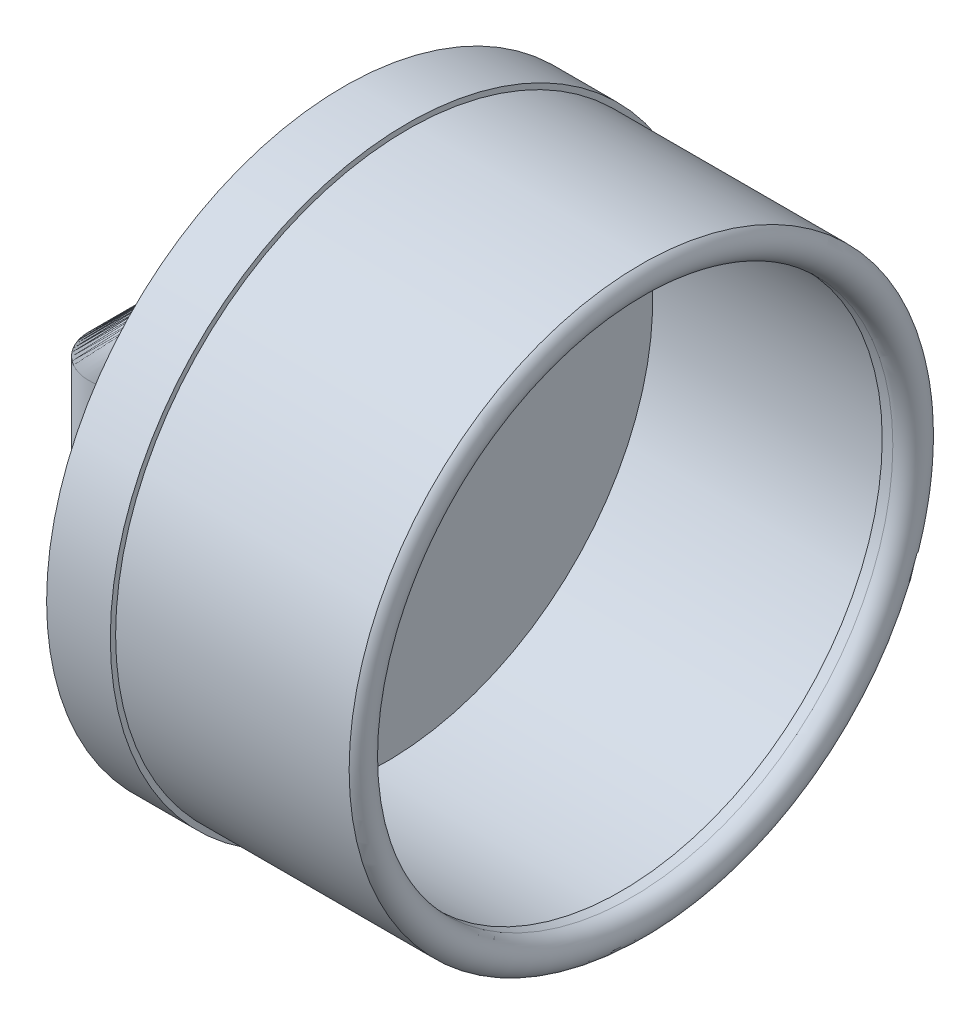
SolidWorks part; units mm, degrees
ref_plane "Front Plane" through (0, 0, 0) normal (0, 0, 1) x (1, 0, 0)
ref_plane "Top Plane" through (0, 0, 0) normal (0, 1, 0) x (1, 0, 0)
ref_plane "Right Plane" through (0, 0, 0) normal (1, 0, 0) x (0, 0, -1)
ref_plane "Plane1" through (0, 0, 0) normal (0, 0, -1) x (-1, 0, 0)
sketch "Sketch1" plane through (0, 0, 0) normal (0, 0, -1) x (-1, 0, 0)
  line L0 (-11.9728, 3.7667) -> (-11.9728, 4.0167)
  line L1 (-11.9728, 4.0167) -> (-0.9121, 4.0167)
  line L2 (-0.9121, 4.0167) -> (-0.9121, 5.4667)
  line L3 (-0.9121, 5.4667) -> (-1.9121, 5.4667)
  line L4 (-1.9121, 5.4667) -> (-1.9121, 5.2167)
  line L5 (-1.9121, 5.2167) -> (-12.9121, 5.2167)
  line L6 (-12.4728, 3.7667) -> (-11.9728, 3.7667)
  line L7 (-12.1757, -8.5333) -> (0.2029, -8.5333) construction
  arc A0 (-12.9121, 5.2167) -> (-12.4728, 3.7667) centre (-12.4728, 4.5583) ccw
  dimension "D1" = 11
  dimension "D2" = 1.45
  dimension "D3" = 0.25
  dimension "D4" = 0.25
  dimension "D5" = 25.1
  dimension "D6" = 1
  dimension "D7" = 0.5
revolve "Revolve1" add sketch "Sketch1" angle 360 about L7
sketch "Sketch2" plane through (0.9121, 0, 0) normal (-1, 0, 0) x (0, 0, 1)
  circle A0 centre (0, -8.5333) radius 14
extrude "Boss-Extrude1" add sketch "Sketch2" along normal blind 2
sketch "Sketch3" plane through (-1.0879, 0, 0) normal (-1, 0, 0) x (0, 0, 1)
  circle A0 centre (0, -8.5333) radius 2
  dimension "D1" = 4
sketch "Sketch4" plane through (0, 0, 0) normal (0, 0, 1) x (1, 0, 0)
  line L0 (-1.0879, -8.5333) -> (-9.0879, -8.5333)
  line L1 (-1.0879, -6.5333) -> (-1.0879, -10.5333) construction
  line L2 (-11.0879, -10.5333) -> (-11.0879, -17.5333)
  arc A0 (-9.0879, -8.5333) -> (-11.0879, -10.5333) centre (-9.0879, -10.5333) ccw
  point P7 (-11.0879, -8.5333)
  dimension "D3" = 2
  dimension "D1" = 10
  dimension "D2" = 9
sweep "Sweep1" add profiles "Sketch3" path "Sketch4"
